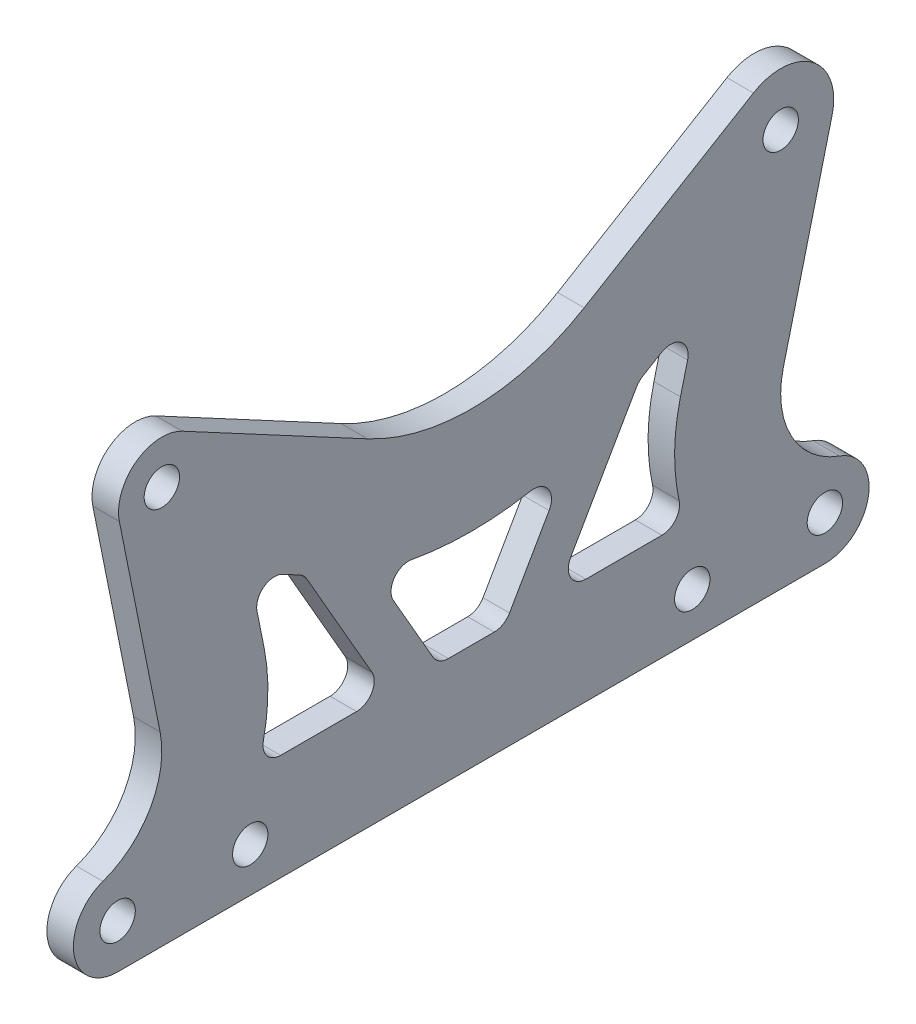
SolidWorks part; units mm, degrees
material "5052-H34"
ref_plane "正面" through (0, 0, 0) normal (0, 0, 1) x (1, 0, 0)
ref_plane "平面" through (0, 0, 0) normal (0, 1, 0) x (1, 0, 0)
ref_plane "右側面" through (0, 0, 0) normal (1, 0, 0) x (0, 0, -1)
sketch "ｽｹｯﾁ1" plane through (0, 0, 0) normal (1, 0, 0) x (0, 0, -1)
  line L1 (75.8191, -1.4622) -> (70.3015, -23.4209)
  line L3 (35, -9.8526) -> (35, -45) construction
  line L4 (-0.1961, -23.887) -> (-4.8039, -0.9657)
  line L9 (66.917, 5.1473) -> (47.7702, -6.3207)
  line L10 (23.2616, -6.9058) -> (2.3144, 4.319)
  line L11 (-5, -45) -> (75, -45)
  arc A8 (66.917, 5.1473) -> (75.8191, -1.4622) centre (70, 0) cw
  arc A9 (2.3144, 4.319) -> (-4.8039, -0.9657) centre (0, 0) ccw
  circle A12 centre (0, 0) radius 2
  circle A13 centre (70, 0) radius 2
  arc A21 (-6.6667, -35.286) -> (-0.1961, -23.887) centre (-10, -25.8579) ccw
  arc A26 (-5, -45) -> (-6.6667, -35.286) centre (-5, -40) cw
  arc A28 (75, -45) -> (76.6667, -35.286) centre (75, -40) ccw
  arc A29 (76.6667, -35.286) -> (70.3015, -23.4209) centre (80, -25.8579) cw
  circle A30 centre (-5, -40) radius 2
  circle A31 centre (75, -40) radius 2
  arc A32 (47.7702, -6.3207) -> (23.2616, -6.9058) centre (35, 15) cw
  circle A33 centre (10, -40) radius 2
  circle A34 centre (60, -40) radius 2
  dimension "D1" = 6
  dimension "D3" = 70
  dimension "D6" = 4
  dimension "D7" = 4
  dimension "D4" = 60
  dimension "D2" = 40
  dimension "D5" = 10
  dimension "D8" = 90
  dimension "D9" = 80
  dimension "D10" = 5
  dimension "D11" = 5
  dimension "D13" = 4
  dimension "D14" = 50
  dimension "D16" = 24.8526
  dimension "D18" = 4.9
  dimension "D12" = 4
extrude "ﾎﾞｽ - 押し出し1" add sketch "ｽｹｯﾁ1" along normal blind 3
sketch "ｽｹｯﾁ4" plane through (3, 0, 0) normal (1, 0, 0) x (0, 0, -1)
  line L0 (16.3885, -17.1801) -> (23.76, -30.0032)
  line L43 (35, -45) -> (35, -9.8526) construction
  line L44 (-5, -45) -> (75, -45) construction
  line L46 (26.1911, -24.1997) -> (30.6733, -31.9968)
  line L47 (43.8089, -24.1997) -> (39.3267, -31.9968)
  line L48 (10.8084, -33) -> (59.1916, -33)
  line L49 (9.9311, -13.3768) -> (11.5685, -21.5221)
  line L50 (58.6633, -20.4965) -> (60.6487, -12.5949)
  line L51 (60.6487, -12.5949) -> (53.9362, -16.6154)
  line L52 (17.5938, -17.4829) -> (9.9311, -13.3768)
  line L53 (13.4427, -33) -> (22.0261, -33)
  line L54 (10.7678, -17.539) -> (11.5685, -21.5221)
  line L55 (58.6633, -20.4965) -> (59.4713, -17.2806)
  line L56 (56.504, -15.0774) -> (54.3829, -16.3478)
  line L57 (15.5992, -16.414) -> (13.6732, -15.382)
  line L58 (53.6767, -17.0669) -> (46.24, -30.0032)
  line L59 (32.4072, -33) -> (37.5928, -33)
  line L60 (47.9739, -33) -> (56.5573, -33)
  arc A0 (59.4713, -17.2806) -> (56.504, -15.0774) centre (57.5316, -16.7932) ccw
  arc A1 (54.3829, -16.3478) -> (53.6767, -17.0669) centre (55.4106, -18.0636) ccw
  arc A3 (58.5109, -30.5715) -> (56.5573, -33) centre (56.5573, -31) cw
  arc A9 (46.24, -30.0032) -> (47.9739, -33) centre (47.9739, -31) ccw
  arc A10 (30.6733, -31.9968) -> (32.4072, -33) centre (32.4072, -31) ccw
  arc A11 (39.3267, -31.9968) -> (37.5928, -33) centre (37.5928, -31) cw
  arc A12 (43.8089, -24.1997) -> (41.7108, -21.2364) centre (42.075, -23.203) ccw
  arc A13 (26.1911, -24.1997) -> (28.2892, -21.2364) centre (27.925, -23.203) cw
  arc A14 (23.76, -30.0032) -> (22.0261, -33) centre (22.0261, -31) cw
  arc A15 (13.4427, -33) -> (11.4891, -30.5715) centre (13.4427, -31) cw
  arc A16 (15.5992, -16.414) -> (16.3885, -17.1801) centre (14.6545, -18.1769) cw
  arc A17 (10.7678, -17.539) -> (13.6732, -15.382) centre (12.7286, -17.1449) cw
  arc A44 (23.2616, -6.9058) -> (47.7702, -6.3207) centre (35, 15) ccw construction
  arc A51 (58.6633, -20.4965) -> (59.1916, -33) centre (80, -25.8579) ccw
  arc A52 (10.8084, -33) -> (11.5685, -21.5221) centre (-10, -25.8579) ccw
  arc A53 (17.5938, -17.4829) -> (53.9362, -16.6154) centre (35, 15) ccw
  arc A54 (58.6633, -20.4965) -> (58.5109, -30.5715) centre (80, -25.8579) ccw
  arc A55 (11.4891, -30.5715) -> (11.5685, -21.5221) centre (-10, -25.8579) ccw
  arc A56 (28.2892, -21.2364) -> (41.7108, -21.2364) centre (35, 15) ccw
  point P26 (44.5173, -33)
  point P29 (31.25, -33)
  point P32 (38.75, -33)
  point P35 (46.1514, -20.1249)
  point P38 (23.8486, -20.1249)
  point P41 (25.4827, -33)
  dimension "D2" = 5
  dimension "D3" = 7.5
  dimension "D4" = 2
  dimension "D1" = 12
extrude "ｶｯﾄ - 押し出し1" cut sketch "ｽｹｯﾁ4" against normal up to surface (3 mm away) up to face at (0, -40, -77)
